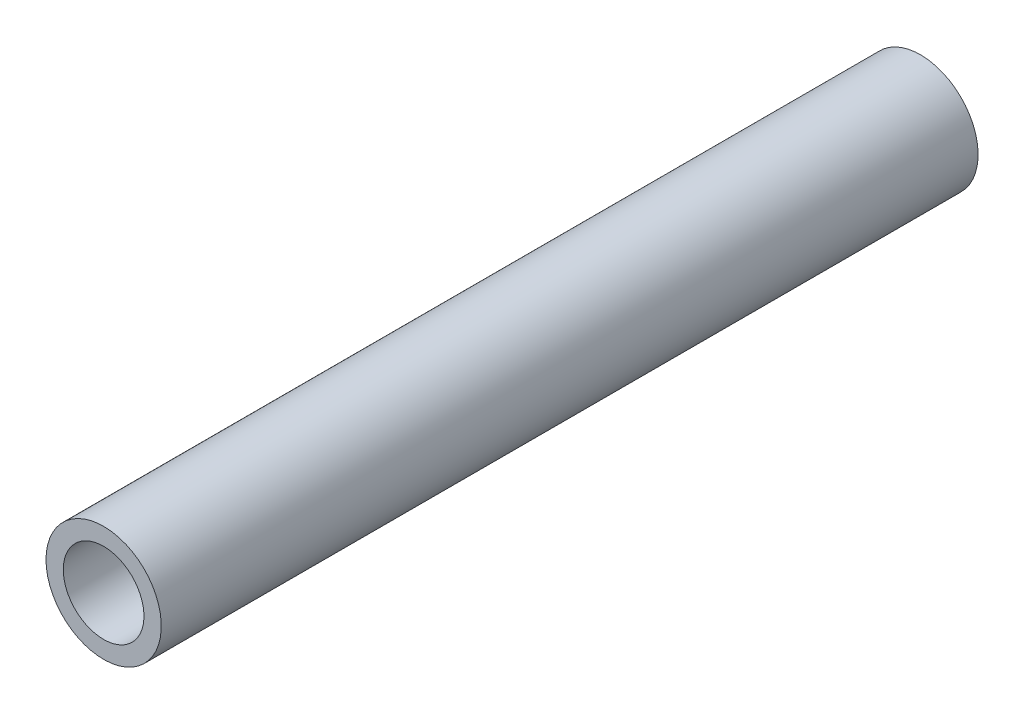
SolidWorks part; units mm, degrees
ref_plane "Front Plane" through (0, 0, 0) normal (0, 0, 1) x (1, 0, 0)
ref_plane "Top Plane" through (0, 0, 0) normal (0, 1, 0) x (1, 0, 0)
ref_plane "Right Plane" through (0, 0, 0) normal (1, 0, 0) x (0, 0, -1)
sketch "Sketch1" plane through (0, 0, 0) normal (0, 0, 1) x (1, 0, 0)
  circle A0 centre (0, 0) radius 4
  circle A1 centre (0, 0) radius 2.8
  dimension "D1" = 8
  dimension "D2" = 1.2
extrude "Boss-Extrude1" add sketch "Sketch1" along normal blind 56.7
